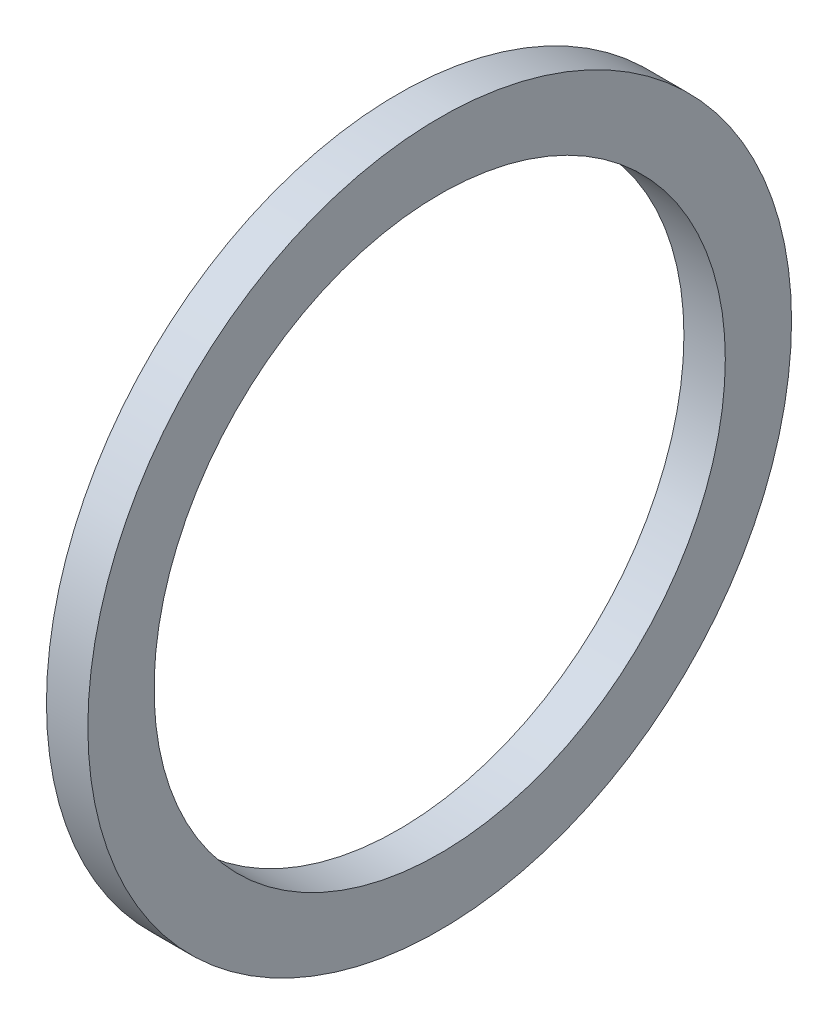
SolidWorks part; units mm, degrees
ref_plane "Front Plane" through (0, 0, 0) normal (0, 0, 1) x (1, 0, 0)
ref_plane "Top Plane" through (0, 0, 0) normal (0, 1, 0) x (1, 0, 0)
ref_plane "Right Plane" through (0, 0, 0) normal (1, 0, 0) x (0, 0, -1)
sketch "Sketch1" plane through (0, 0, 0) normal (1, 0, 0) x (0, 0, -1)
  circle A0 centre (0, 0) radius 6.9
  circle A1 centre (0, 0) radius 8.5
  dimension "D1" = 13.8
  dimension "D2" = 17
extrude "Boss-Extrude1" add sketch "Sketch1" along normal blind 1
